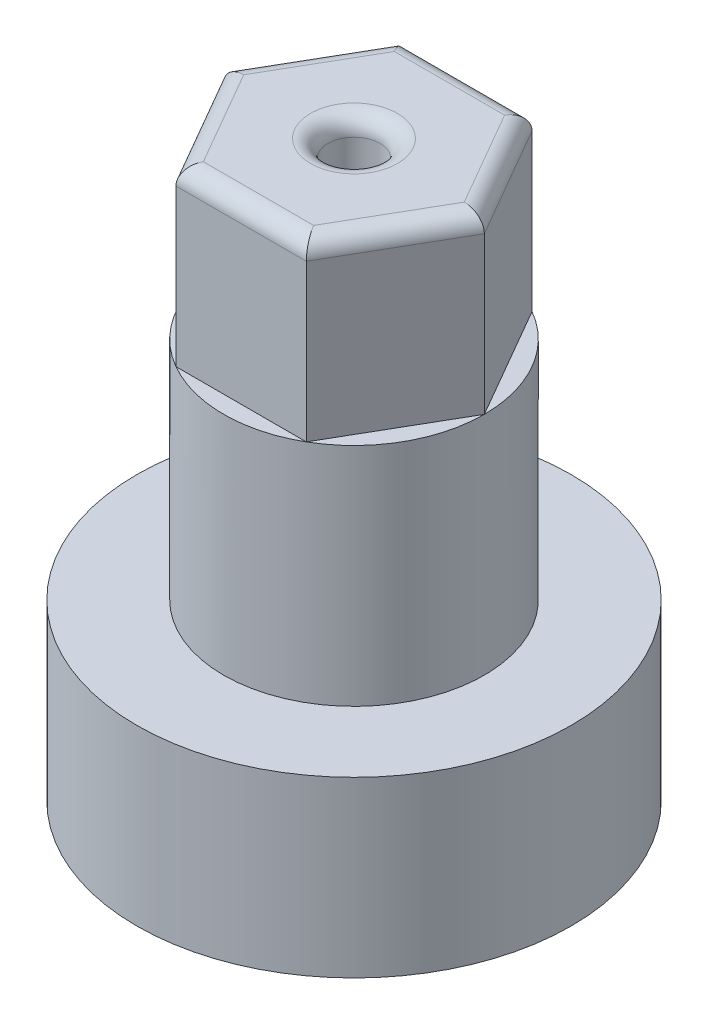
SolidWorks part; units mm, degrees
ref_plane "Alzado" through (0, 0, 0) normal (0, 0, 1) x (1, 0, 0)
ref_plane "Planta" through (0, 0, 0) normal (0, 1, 0) x (1, 0, 0)
ref_plane "Vista lateral" through (0, 0, 0) normal (1, 0, 0) x (0, 0, -1)
sketch "Croquis1" plane through (0, 0, 0) normal (0, 1, 0) x (1, 0, 0)
  line L0 (-12.5, 0) -> (12.5, 0) construction
  circle A0 centre (0, 0) radius 12.5
  circle A1 centre (7, 0) radius 0.75
  circle A2 centre (0, -7) radius 0.75
  circle A3 centre (-7, 0) radius 0.75
  circle A4 centre (0, 7) radius 0.75
  point P16 (0, 0)
  dimension "D1" = 25
  dimension "D2" = 1.5
  dimension "D3" = 7
  dimension "D4" = 4
extrude "Saliente-Extruir1" add sketch "Croquis1" along normal blind 10
sketch "Croquis2" plane through (0, 10, 0) normal (0, 1, 0) x (1, 0, 0)
  circle A0 centre (0, 0) radius 7.5
  dimension "D1" = 15
extrude "Saliente-Extruir2" add sketch "Croquis2" along normal blind 13
sketch "Croquis5" plane through (0, 10, 0) normal (0, 1, 0) x (1, 0, 0)
  circle A0 centre (0, 0) radius 12.5
extrude "Saliente-Extruir4" add sketch "Croquis5" against normal blind 1
sketch "Croquis3" plane through (0, 23, 0) normal (0, 1, 0) x (1, 0, 0)
  line L1 (7.5, 0) -> (3.75, 6.4952)
  line L2 (3.75, 6.4952) -> (-3.75, 6.4952)
  line L3 (-3.75, 6.4952) -> (-7.5, 0)
  line L4 (-7.5, 0) -> (-3.75, -6.4952)
  line L5 (-3.75, -6.4952) -> (3.75, -6.4952)
  line L6 (3.75, -6.4952) -> (7.5, 0)
  circle A0 centre (0, 0) radius 7.5 construction
extrude "Saliente-Extruir3" add sketch "Croquis3" along normal blind 10
sketch "Croquis4" plane through (0, 33, 0) normal (0, 1, 0) x (1, 0, 0)
  circle A0 centre (0, 0) radius 1.5
  dimension "D1" = 3
extrude "Cortar-Extruir1" cut sketch "Croquis4" against normal through all
fillet "Redondeo1" radius 1 7 edges at (0, 33, 6.4952) (-5.625, 33, 3.2476) (-5.625, 33, -3.2476) (0, 33, -6.4952) (5.625, 33, -3.2476) (5.625, 33, 3.2476) (0, 33, 1.5)
